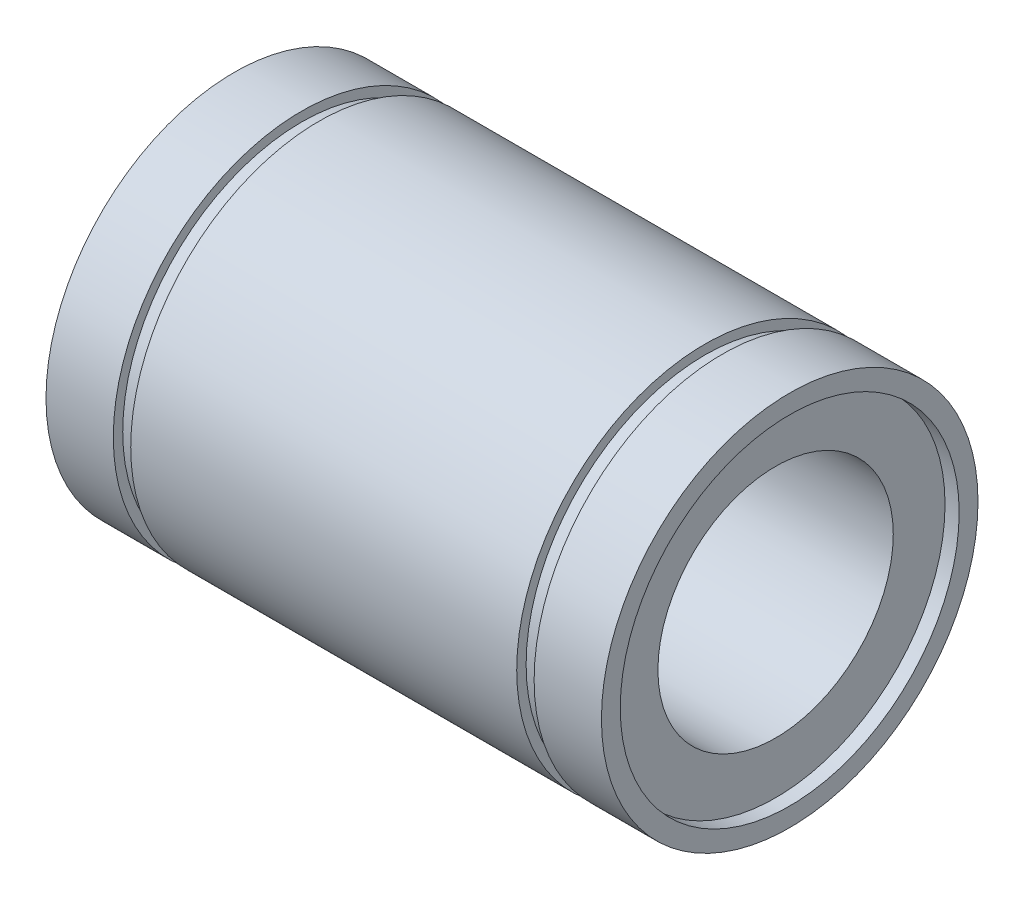
SolidWorks part; units mm, degrees
ref_plane "Płaszczyzna przednia" through (0, 0, 0) normal (0, 0, 1) x (1, 0, 0)
ref_plane "Płaszczyzna górna" through (0, 0, 0) normal (0, 1, 0) x (1, 0, 0)
ref_plane "Płaszczyzna prawa" through (0, 0, 0) normal (1, 0, 0) x (0, 0, -1)
sketch "Szkic1" plane through (0, 0, 0) normal (0, 0, 1) x (1, 0, 0)
  line L0 (0, 22.2025) -> (0, -17.9396) construction
  line L1 (-34.3709, 0) -> (40.5846, 0) construction
  line L2 (20.5, 20) -> (-20.5, 20)
  line L3 (-29.5, 20) -> (-29.5, 18)
  line L4 (-29.5, 18) -> (-28, 18)
  line L5 (-28, 18) -> (-28, 12.5)
  line L6 (-28, 12.5) -> (28, 12.5)
  line L7 (-20.5, 20) -> (-20.5, 19)
  line L8 (-20.5, 19) -> (-22.35, 19)
  line L9 (-22.35, 19) -> (-22.35, 20)
  line L10 (-22.35, 20) -> (-29.5, 20)
  line L11 (22.35, 20) -> (29.5, 20)
  line L12 (22.35, 19) -> (22.35, 20)
  line L13 (20.5, 19) -> (22.35, 19)
  line L14 (20.5, 20) -> (20.5, 19)
  line L15 (28, 18) -> (28, 12.5)
  line L16 (29.5, 18) -> (28, 18)
  line L17 (29.5, 20) -> (29.5, 18)
  point P13 (-20.5, 19.5)
  point P22 (0, 12.5)
  point P24 (0, 20)
  dimension "D1" = 40
  dimension "D2" = 59
  dimension "D3" = 41
  dimension "D4" = 1.85
  dimension "D5" = 25
  dimension "D6" = 38
  dimension "D7" = 1.5
  dimension "D8" = 2
revolve "Obrót1" add sketch "Szkic1" angle 360 about L1
